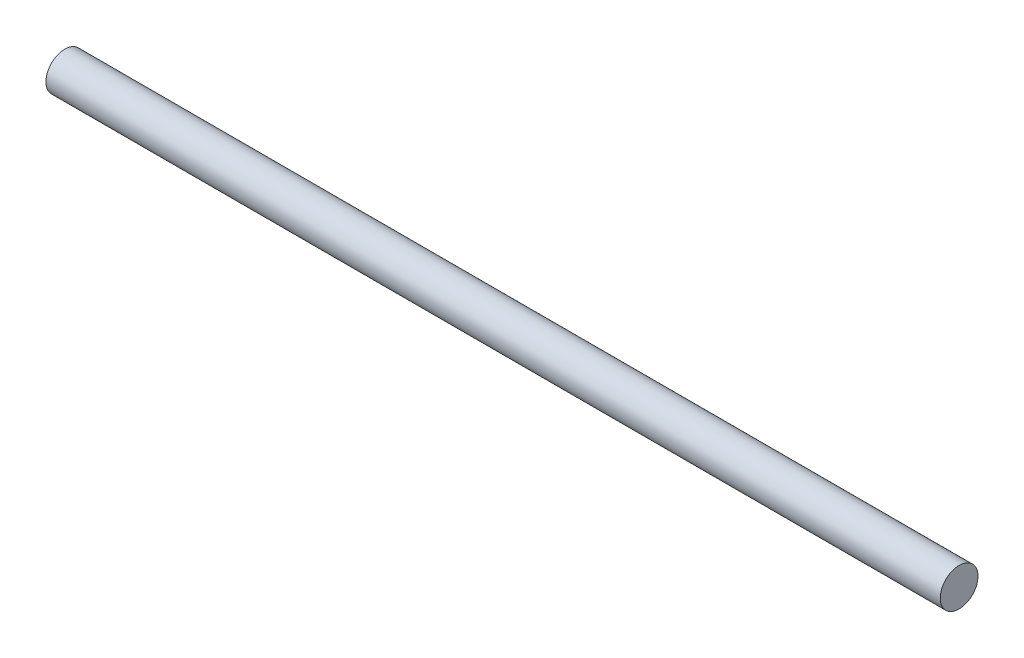
SolidWorks part; units mm, degrees
ref_plane "Plano frontal" through (0, 0, 0) normal (0, 0, 1) x (1, 0, 0)
ref_plane "Plano superior" through (0, 0, 0) normal (0, 1, 0) x (1, 0, 0)
ref_plane "Plano direito" through (0, 0, 0) normal (1, 0, 0) x (0, 0, -1)
sketch "Esboço1" plane through (0, 0, 0) normal (1, 0, 0) x (0, 0, -1)
  circle A0 centre (0, 0) radius 1.5
  dimension "D1" = 3
extrude "Ressalto-extrusão1" add sketch "Esboço1" along normal blind 71
